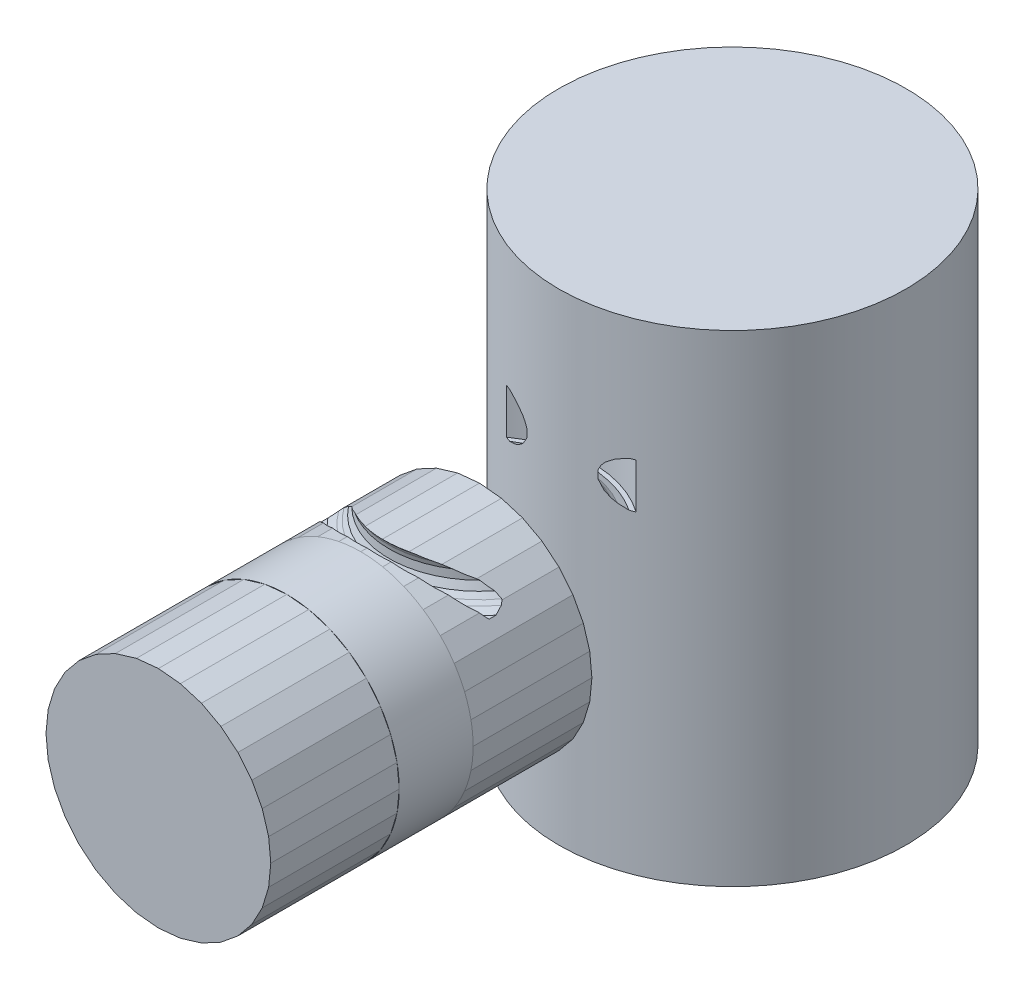
SolidWorks part; units mm, degrees
ref_plane "Front Plane" through (0, 0, 0) normal (0, 0, 1) x (1, 0, 0)
ref_plane "Top Plane" through (0, 0, 0) normal (0, 1, 0) x (1, 0, 0)
ref_plane "Right Plane" through (0, 0, 0) normal (1, 0, 0) x (0, 0, -1)
sketch "CADView Core Profile" plane through (0, 0, 0) normal (0, 0, 1) x (1, 0, 0)
  line L1 (-7, 0) -> (-6.8655, -1.3656)
  line L2 (-6.8655, -1.3656) -> (-6.4672, -2.6788)
  line L3 (-6.4672, -2.6788) -> (-5.8203, -3.889)
  line L4 (-5.8203, -3.889) -> (-4.9497, -4.9497)
  line L5 (-4.9497, -4.9497) -> (-3.889, -5.8203)
  line L6 (-3.889, -5.8203) -> (-2.6788, -6.4672)
  line L7 (-2.6788, -6.4672) -> (-1.3656, -6.8655)
  line L8 (-1.3656, -6.8655) -> (0, -7)
  line L9 (0, -7) -> (1.3656, -6.8655)
  line L10 (1.3656, -6.8655) -> (2.6788, -6.4672)
  line L11 (2.6788, -6.4672) -> (3.889, -5.8203)
  line L12 (3.889, -5.8203) -> (4.9497, -4.9497)
  line L13 (4.9497, -4.9497) -> (5.8203, -3.889)
  line L14 (5.8203, -3.889) -> (6.4672, -2.6788)
  line L15 (6.4672, -2.6788) -> (6.8655, -1.3656)
  line L16 (6.8655, -1.3656) -> (7, 0)
  line L17 (7, 0) -> (6.8655, 1.3656)
  line L18 (6.8655, 1.3656) -> (6.4672, 2.6788)
  line L19 (6.4672, 2.6788) -> (5.8203, 3.889)
  line L20 (5.8203, 3.889) -> (4.9497, 4.9497)
  line L21 (4.9497, 4.9497) -> (3.889, 5.8203)
  line L22 (3.889, 5.8203) -> (2.6788, 6.4672)
  line L23 (2.6788, 6.4672) -> (1.3656, 6.8655)
  line L24 (1.3656, 6.8655) -> (0, 7)
  line L25 (0, 7) -> (-1.3656, 6.8655)
  line L26 (-1.3656, 6.8655) -> (-2.6788, 6.4672)
  line L27 (-2.6788, 6.4672) -> (-3.889, 5.8203)
  line L28 (-3.889, 5.8203) -> (-4.9497, 4.9497)
  line L29 (-4.9497, 4.9497) -> (-5.8203, 3.889)
  line L30 (-5.8203, 3.889) -> (-6.4672, 2.6788)
  line L31 (-6.4672, 2.6788) -> (-6.8655, 1.3656)
  line L32 (-6.8655, 1.3656) -> (-7, 0)
extrude "CADView Core Extrude" add sketch "CADView Core Profile" along normal blind 20
sketch "CADView Residual Boss Profile 1" plane through (0, 0, 0) normal (0, 1, 0) x (1, 0, 0)
  circle A0 centre (0, 15.7546) radius 10.8154
extrude "CADView Residual Boss 1" add sketch "CADView Residual Boss Profile 1" along normal blind 30 from offset 15
sketch "CADView Residual Cut Profile 2" plane through (0, 0, 0) normal (1, 0, 0) x (0, 0, -1)
  line L1 (-15, 7.4) -> (-15, 12)
  line L2 (-15, 12) -> (15, 12)
  line L3 (15, 12) -> (15, 7.4)
  line L4 (15, 7.4) -> (-15, 7.4)
extrude "CADView Residual Cut 2" cut sketch "CADView Residual Cut Profile 2" against normal blind 20 from offset 10
sketch "CADView Residual Boss Profile 3" plane through (0, 0, 0) normal (0, 0, 1) x (1, 0, 0)
  circle A0 centre (0, 0) radius 7
extrude "CADView Residual Boss 3" add sketch "CADView Residual Boss Profile 3" along normal blind 4.6033 from offset 7.3967
sketch "CADView Residual Revolve Cut Profile 4" plane through (0, 0, 0) normal (1, 0, 0) x (0, 0, -1)
  line L1 (7, 4.6) -> (7, 7.4)
  line L2 (7, 7.4) -> (6.7194, 7.4)
  line L3 (6.7194, 7.4) -> (6.1898, 7.1375)
  line L4 (6.1898, 7.1375) -> (5.8439, 6.7875)
  line L5 (5.8439, 6.7875) -> (5.7164, 6.5542)
  line L6 (5.7164, 6.5542) -> (5.6259, 6.2625)
  line L7 (5.6259, 6.2625) -> (5.6259, 5.7375)
  line L8 (5.6259, 5.7375) -> (5.8099, 5.2708)
  line L9 (5.8099, 5.2708) -> (6.0477, 4.9792)
  line L10 (6.0477, 4.9792) -> (6.2816, 4.8042)
  line L11 (6.2816, 4.8042) -> (6.7194, 4.6)
  line L12 (6.7194, 4.6) -> (7, 4.6)
  line L13 (0, 4.46) -> (0, 7.54) construction
revolve "CADView Residual Revolve Cut 4" cut sketch "CADView Residual Revolve Cut Profile 4" angle 360 about L13
